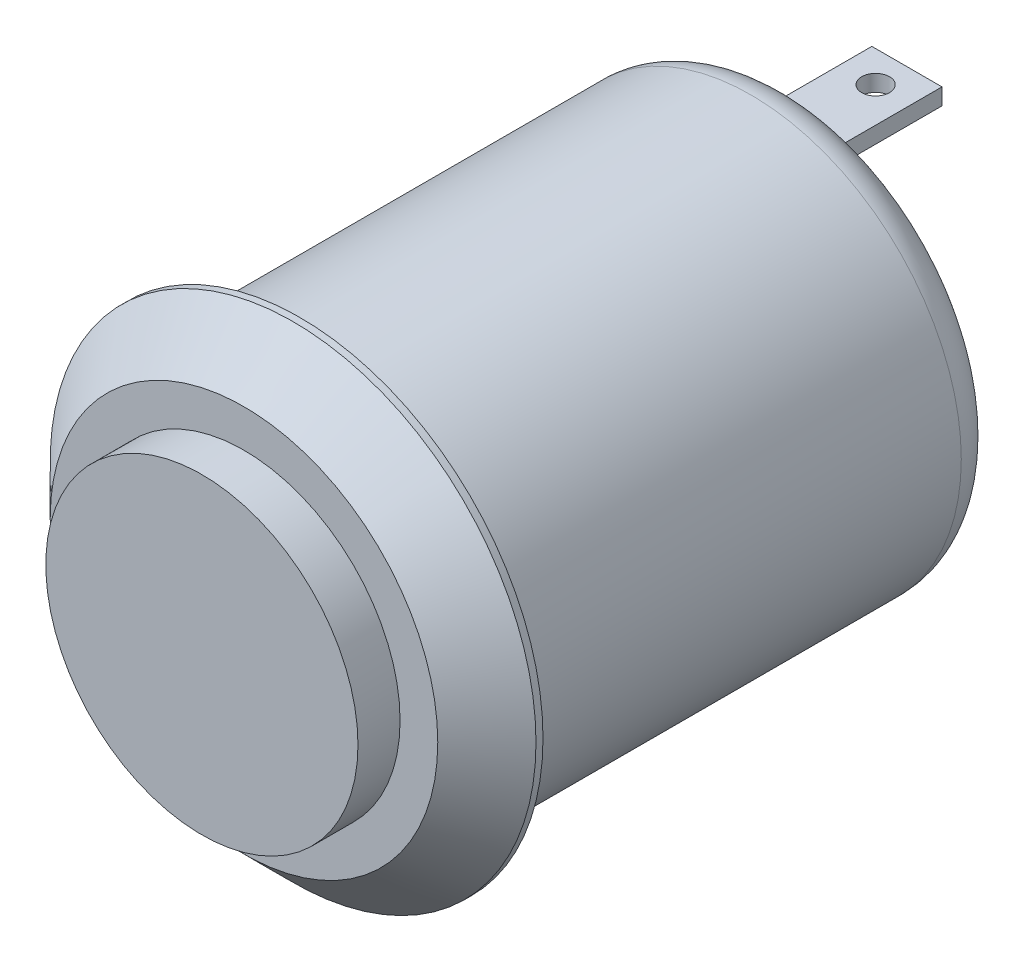
SolidWorks part; units mm, degrees
ref_plane "Front Plane" through (0, 0, 0) normal (0, 0, 1) x (1, 0, 0)
ref_plane "Top Plane" through (0, 0, 0) normal (0, 1, 0) x (1, 0, 0)
ref_plane "Right Plane" through (0, 0, 0) normal (1, 0, 0) x (0, 0, -1)
sketch "Sketch1" plane through (0, 0, 0) normal (0, 0, 1) x (1, 0, 0)
  circle A0 centre (0, 0) radius 6
  dimension "D1" = 12
extrude "Boss-Extrude1" add sketch "Sketch1" against normal blind 14
sketch "Sketch2" plane through (0, 0, 0) normal (0, 0, 1) x (1, 0, 0)
  circle A0 centre (0, 0) radius 6.925
  dimension "D1" = 13.85
extrude "Boss-Extrude2" add sketch "Sketch2" along normal blind 1.6
chamfer "Chamfer1" distance 1.4 1 edges at (6.925, 0, 1.6)
sketch "Sketch3" plane through (0, 0, 1.6) normal (0, 0, 1) x (1, 0, 0)
  circle A0 centre (0, 0) radius 4.45
  dimension "D1" = 8.9
extrude "Boss-Extrude3" add sketch "Sketch3" along normal blind 1.2
fillet "Fillet1" radius 1.15 1 edges at (6, 0, -14)
sketch "Sketch5" plane through (0, 0, -14) normal (0, 0, -1) x (-1, 0, 0)
  line L0 (0, 0) -> (-1.7573, 0) construction
  line L1 (0, 0) -> (0, -0.83) construction
  line L2 (-1, -4) -> (1, -4)
  line L3 (-1, 4) -> (1, 4)
  line L4 (-1, 4) -> (-1, 4.47)
  line L5 (-1, 4.47) -> (1, 4.47)
  line L6 (1, 4) -> (1, 4.47)
  line L7 (-1, 4) -> (1, 4.47) construction
  line L8 (-1, 4.47) -> (1, 4) construction
  line L9 (1, -4) -> (1, -4.47)
  line L10 (-1, -4) -> (-1, -4.47)
  line L11 (-1, -4.47) -> (1, -4.47)
  point P3 (0, 4.235)
  point P9 (0, 0)
  dimension "D1" = 0.47
  dimension "D2" = 4
  dimension "D3" = 2
extrude "Boss-Extrude4" add sketch "Sketch5" along normal blind 3.3
sketch "Sketch6" plane through (0, 4.47, 0) normal (0, 1, 0) x (1, 0, 0)
  circle A0 centre (0, 16.408) radius 0.3954
extrude "Cut-Extrude1" cut sketch "Sketch6" against normal through all
